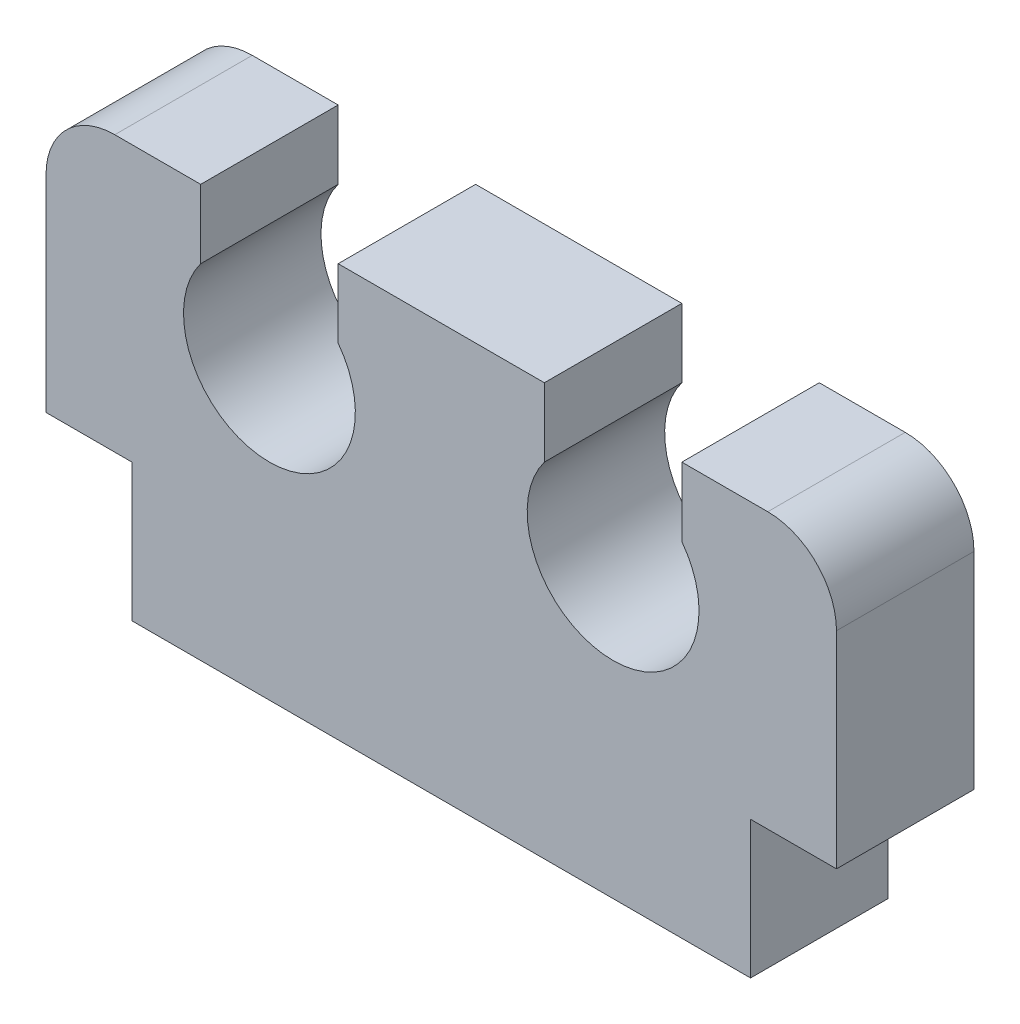
SolidWorks part; units mm, degrees
material "Acrylic (Medium-high impact)"
ref_plane "Front Plane" through (0, 0, 0) normal (0, 0, 1) x (1, 0, 0)
ref_plane "Top Plane" through (0, 0, 0) normal (0, 1, 0) x (1, 0, 0)
ref_plane "Right Plane" through (0, 0, 0) normal (1, 0, 0) x (0, 0, -1)
sketch "Model" plane through (0, 0, 0) normal (0, 0, 1) x (1, 0, 0)
  line L268 (1971.6098, 1160.8936) -> (1971.6098, 1159.8936)
  line L269 (1973.6098, 1160.8936) -> (1973.6098, 1159.8936)
  line L270 (1978.6098, 1160.8936) -> (1978.6098, 1159.8936)
  line L271 (1976.6098, 1160.8936) -> (1976.6098, 1159.8936)
  line L272 (1980.8598, 1156.8936) -> (1980.8598, 1159.8936)
  line L273 (1969.3598, 1156.8936) -> (1969.3598, 1159.8936)
  line L280 (1970.6098, 1156.8936) -> (1969.3598, 1156.8936)
  line L281 (1979.6098, 1156.8936) -> (1980.8598, 1156.8936)
  line L282 (1971.6098, 1160.8936) -> (1970.3598, 1160.8936)
  line L283 (1978.6098, 1160.8936) -> (1979.8598, 1160.8936)
  line L342 (1970.6098, 1154.8936) -> (1979.6098, 1154.8936)
  line L343 (1973.6098, 1160.8936) -> (1976.6098, 1160.8936)
  line L344 (1970.6098, 1156.8936) -> (1970.6098, 1154.8936)
  line L345 (1979.6098, 1156.8936) -> (1979.6098, 1154.8936)
  arc A77 (1971.6098, 1159.8936) -> (1973.6098, 1159.8936) centre (1972.6098, 1159.1436) ccw
  arc A78 (1976.6098, 1159.8936) -> (1978.6098, 1159.8936) centre (1977.6098, 1159.1436) ccw
  arc A79 (1980.8598, 1159.8936) -> (1979.8598, 1160.8936) centre (1979.8598, 1159.8936) ccw
  arc A80 (1970.3598, 1160.8936) -> (1969.3598, 1159.8936) centre (1970.3598, 1159.8936) ccw
extrude "Boss-Extrude1" add sketch "Model" along normal blind 2
